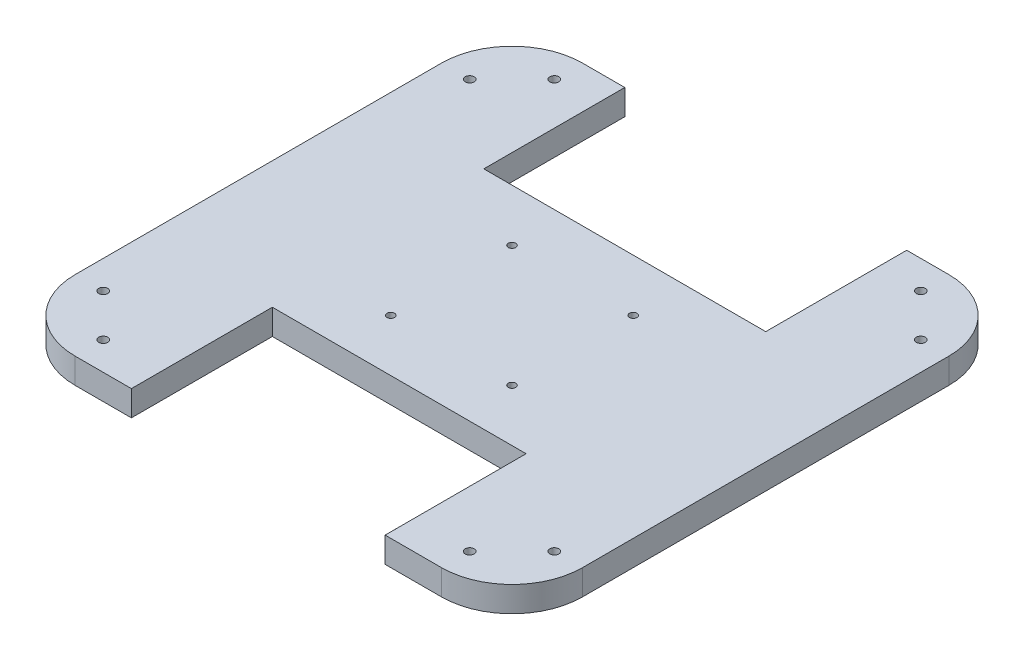
SolidWorks part; units mm, degrees
ref_plane "Front Plane" through (0, 0, 0) normal (0, 0, 1) x (1, 0, 0)
ref_plane "Top Plane" through (0, 0, 0) normal (0, 1, 0) x (1, 0, 0)
ref_plane "Right Plane" through (0, 0, 0) normal (1, 0, 0) x (0, 0, -1)
sketch "Sketch1" plane through (0, 0, 0) normal (0, 1, 0) x (1, 0, 0)
  line L1 (-65, -90) -> (65, -90)
  line L2 (-90, -65) -> (-90, 65)
  line L3 (-65, 90) -> (65, 90)
  line L4 (90, -65) -> (90, 65)
  arc A0 (-90, 65) -> (-65, 90) centre (-65, 65) cw
  arc A1 (65, 90) -> (90, 65) centre (65, 65) cw
  arc A2 (90, -65) -> (65, -90) centre (65, -65) cw
  arc A3 (-65, -90) -> (-90, -65) centre (-65, -65) cw
  point P4 (-90, 0)
  point P6 (0, 90)
  dimension "D3" = 25
  dimension "D1" = 180
  dimension "D2" = 180
extrude "Plate" add sketch "Sketch1" along normal blind 9
sketch "Sketch3" plane through (0, 9, 0) normal (0, 1, 0) x (1, 0, 0)
  line L0 (-65, 90) -> (-65, -90) construction
  line L1 (65, 90) -> (65, -90) construction
  line L2 (-90, 65) -> (90, 65) construction
  line L3 (-90, -65) -> (90, -65) construction
  circle A0 centre (-65, 80) radius 1.6
  circle A1 centre (-80, 65) radius 1.6
  circle A2 centre (80, 65) radius 1.6
  circle A3 centre (80, -65) radius 1.6
  circle A4 centre (65, 80) radius 1.6
  circle A5 centre (65, -80) radius 1.6
  circle A6 centre (-65, -80) radius 1.6
  circle A7 centre (-80, -65) radius 1.6
  dimension "D1" = 3.2
  dimension "D2" = 15
  dimension "D3" = 15
  dimension "D4" = 15
  dimension "D5" = 15
  dimension "D6" = 15
  dimension "D7" = 15
  dimension "D8" = 15
  dimension "D9" = 15
extrude "Hex Holes" cut sketch "Sketch3" against normal through all
sketch "Sketch4" plane through (0, 9, 0) normal (0, 1, 0) x (1, 0, 0)
  line L0 (-90, -65) -> (-90, 65) construction
  line L1 (-65, -90) -> (65, -90) construction
  circle A0 centre (-21.5, 21.5) radius 1.325
  circle A1 centre (21.5, 21.5) radius 1.325
  circle A2 centre (21.5, -21.5) radius 1.325
  circle A3 centre (-21.5, -21.5) radius 1.325
  dimension "D1" = 2.65
  dimension "D2" = 43
  dimension "D3" = 43
  dimension "D4" = 68.5
  dimension "D5" = 68.5
extrude "LiDAR Holes" cut sketch "Sketch4" against normal through all
sketch "Sketch5" plane through (0, 9, 0) normal (0, 1, 0) x (1, 0, 0)
  line L0 (-65, 90) -> (65, 90) construction
  line L1 (50, 90) -> (-50, 90)
  line L2 (50, 90) -> (50, 40)
  line L3 (50, 40) -> (-50, 40)
  line L4 (-50, 90) -> (-50, 40)
  line L5 (-65, -90) -> (65, -90) construction
  line L6 (45, -90) -> (-45, -90)
  line L7 (45, -90) -> (45, -40)
  line L8 (45, -40) -> (-45, -40)
  line L9 (-45, -90) -> (-45, -40)
  point P6 (0, 90)
  point P7 (0, 90)
  point P14 (0, -90)
  point P15 (0, -90)
  dimension "D1" = 100
  dimension "D2" = 50
  dimension "D3" = 50
  dimension "D4" = 90
extrude "Cut-Extrude1" cut sketch "Sketch5" against normal through all
sketch "Sketch6" plane through (0, 0, 0) normal (0, -1, 0) x (1, 0, 0)
  circle A0 centre (-21.5, 21.5) radius 3.5
  circle A1 centre (21.5, 21.5) radius 3.5
  circle A2 centre (-21.5, -21.5) radius 3.5
  circle A3 centre (21.5, -21.5) radius 3.5
  dimension "D1" = 7
extrude "Cut-Extrude2" cut sketch "Sketch6" against normal blind 5
